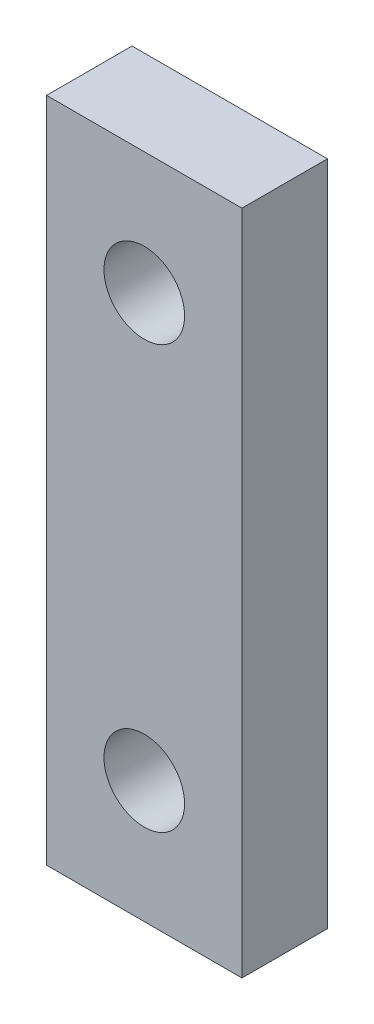
SolidWorks part; units mm, degrees
ref_plane "Front Plane" through (0, 0, 0) normal (0, 0, 1) x (1, 0, 0)
ref_plane "Top Plane" through (0, 0, 0) normal (0, 1, 0) x (1, 0, 0)
ref_plane "Right Plane" through (0, 0, 0) normal (1, 0, 0) x (0, 0, -1)
sketch "Sketch1" plane through (0, 0, 0) normal (0, 0, 1) x (1, 0, 0)
  line L1 (0, 0) -> (8, 0)
  line L2 (0, 0) -> (0, 27.3)
  line L3 (0, 27.3) -> (8, 27.3)
  line L4 (8, 0) -> (8, 27.3)
  line L5 (4, 5) -> (4, 0) construction
  line L6 (4, 22.3) -> (4, 27.3) construction
  circle A0 centre (4, 22.3) radius 1.65
  circle A1 centre (4, 5) radius 1.65
  dimension "D2" = 3.3
  dimension "D3" = 3.3
  dimension "D1" = 17.3
  dimension "D4" = 5
  dimension "D5" = 8
extrude "Boss-Extrude1" add sketch "Sketch1" along normal blind 3.5
